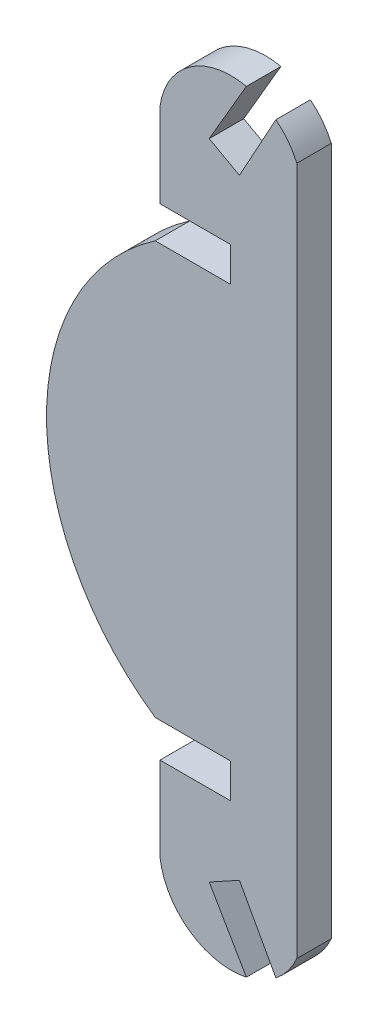
SolidWorks part; units mm, degrees
ref_plane "Front" through (0, 0, 0) normal (0, 0, 1) x (1, 0, 0)
ref_plane "Top" through (0, 0, 0) normal (0, 1, 0) x (1, 0, 0)
ref_plane "Right" through (0, 0, 0) normal (1, 0, 0) x (0, 0, -1)
sketch "Sketch1" plane through (0, 0, 0) normal (0, 0, 1) x (1, 0, 0)
  line L0 (195.1673, -118.6727) -> (198.339, -124.4459)
  line L1 (192.5379, -120.1172) -> (195.1673, -118.6727)
  line L2 (192.5379, -120.1172) -> (195.772, -125.6689)
  line L3 (194.3869, -113.0727) -> (194.3869, -110.0727)
  line L4 (194.3869, -110.0727) -> (187.8432, -110.0727)
  line L5 (194.3869, -113.0727) -> (188.2585, -113.0727)
  line L6 (188.2585, -113.0727) -> (188.2585, -120.4088)
  line L8 (200.1584, -122.0748) -> (200.1584, -62.1706)
  line L9 (188.2585, -71.1727) -> (188.2585, -63.8366)
  line L10 (194.3869, -71.1727) -> (188.2585, -71.1727)
  line L11 (194.3869, -74.1727) -> (187.8432, -74.1727)
  line L12 (194.3869, -71.1727) -> (194.3869, -74.1727)
  line L13 (192.5379, -64.1281) -> (195.772, -58.5764)
  line L14 (192.5379, -64.1281) -> (195.1673, -65.5727)
  line L15 (195.1673, -65.5727) -> (198.339, -59.7994)
  line L16 (178.39, -92.1227) -> (200.1584, -92.1227) construction
  arc A0 (200.1584, -122.0748) -> (198.339, -124.4459) centre (194.4422, -119.5722) cw
  arc A1 (195.772, -125.6689) -> (188.2585, -120.4088) centre (194.4422, -119.5722) cw
  arc A2 (187.8432, -74.1727) -> (187.8432, -110.0727) centre (200.1584, -92.1227) ccw
  arc A4 (195.772, -58.5764) -> (188.2585, -63.8366) centre (194.4422, -64.6732) ccw
  arc A6 (200.1584, -62.1706) -> (198.339, -59.7994) centre (194.4422, -64.6732) ccw
  dimension "D1" = 3
  dimension "D2" = 17.95
  dimension "D4" = 3
extrude "Base-Extrude" add sketch "Sketch1" along normal blind 3
